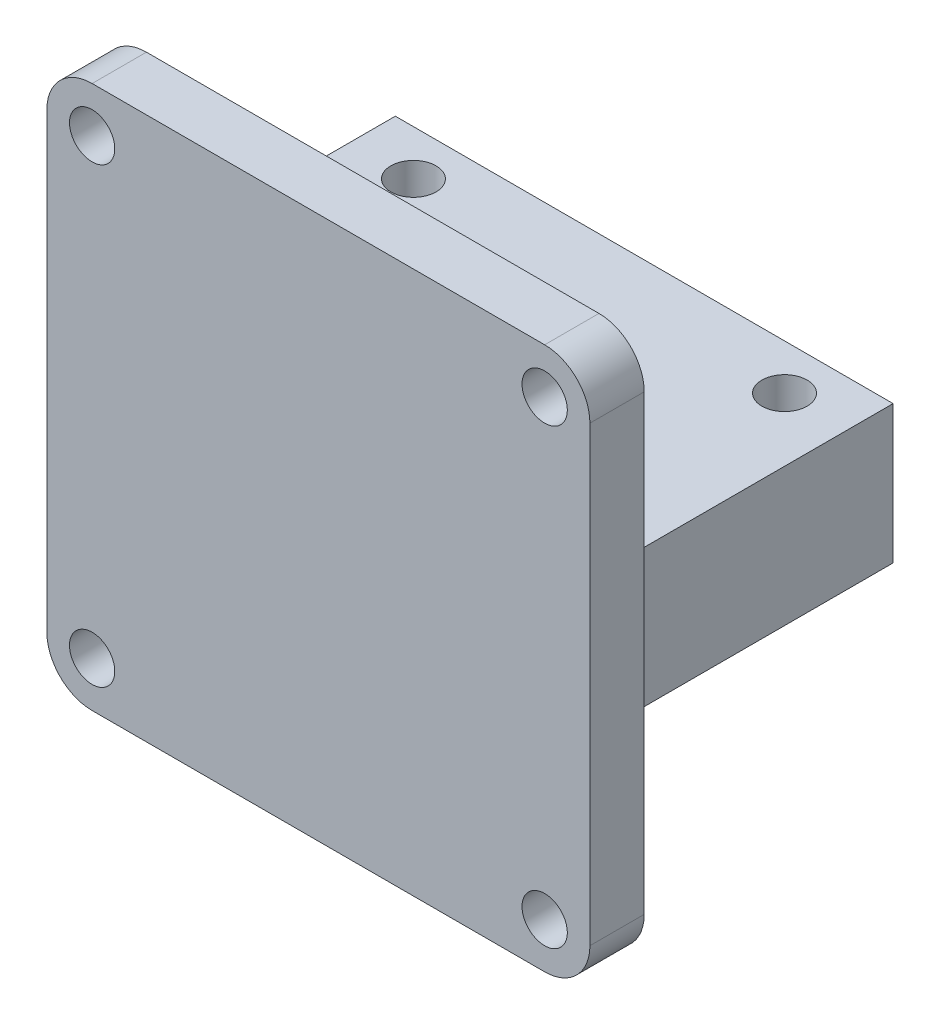
SolidWorks part; units mm, degrees
ref_plane "Front Plane" through (0, 0, 0) normal (0, 0, 1) x (1, 0, 0)
ref_plane "Top Plane" through (0, 0, 0) normal (0, 1, 0) x (1, 0, 0)
ref_plane "Right Plane" through (0, 0, 0) normal (1, 0, 0) x (0, 0, -1)
sketch "Sketch1" plane through (0, 0, 0) normal (0, 0, 1) x (1, 0, 0)
  line L1 (-30, 30) -> (30, 30)
  line L2 (-30, 30) -> (-30, -30)
  line L3 (-30, -30) -> (30, -30)
  line L4 (30, 30) -> (30, -30)
  line L5 (-30, 30) -> (30, -30) construction
  line L6 (-30, -30) -> (30, 30) construction
  point P0 (0, 0)
  dimension "D1" = 60
  dimension "D2" = 60
extrude "Boss-Extrude1" add sketch "Sketch1" along normal blind 6
sketch "Sketch2" plane through (0, 0, 0) normal (0, 0, -1) x (-1, 0, 0)
  line L1 (-27.5, 7.625) -> (27.5, 7.625)
  line L2 (-27.5, 7.625) -> (-27.5, -7.625)
  line L3 (-27.5, -7.625) -> (27.5, -7.625)
  line L4 (27.5, 7.625) -> (27.5, -7.625)
  line L5 (-27.5, 7.625) -> (27.5, -7.625) construction
  line L6 (-27.5, -7.625) -> (27.5, 7.625) construction
  point P0 (0, 0)
  dimension "D1" = 15.25
  dimension "D2" = 55
extrude "Boss-Extrude2" add sketch "Sketch2" along normal blind 30
hole_wizard "Ø5.0mm Dowel Hole1" positions "Sketch5" profile "Sketch6" hole size "Ø5.0" standard "DIN" end condition through all
sketch "Sketch5" plane through (0, 0, 0) normal (0, 0, -1) x (-1, 0, 0)
  line L0 (0, 30) -> (0, -30) construction
  line L1 (-30, 30) -> (30, 30) construction
  line L2 (30, -30) -> (-30, -30) construction
  line L4 (-30, 0) -> (30, 0) construction
  line L5 (-30, -30) -> (-30, 30) construction
  line L6 (30, 30) -> (30, -30) construction
  point P0 (25, 25)
  point P19 (0, 0)
  point P20 (-25, 25)
  point P21 (25, -25)
  point P22 (-25, -25)
  dimension "D1" = 5
  dimension "D2" = 5
sketch "Sketch6" plane through (-25, 25, 0) normal (1, 0, 0) x (0, 1, 0)
  line L0 (0, 0) -> (0, 6)
  line L1 (0, 6) -> (2.5, 6)
  line L2 (2.5, 6) -> (2.5, 0)
  line L5 (2.5, 0) -> (0, 0)
  line L11 (0, -6.35) -> (0, 107.95) construction
  dimension "Thru Hole Dia." = 5
  dimension "Thru Hole Depth" = 6
fillet "Fillet1" radius 5 4 edges at (-30, 30, 3) (-30, -30, 3) (30, -30, 3) (30, 30, 3)
hole_wizard "Ø5.0mm Dowel Hole2" positions "Sketch7" profile "Sketch8" hole size "Ø5.0" standard "DIN" end condition through all
sketch "Sketch7" plane through (0, 7.625, 0) normal (0, 1, 0) x (1, 0, 0)
  line L0 (27.5, 15) -> (-27.5, 15) construction
  line L1 (27.5, 30) -> (27.5, 0) construction
  line L2 (-27.5, 30) -> (-27.5, 0) construction
  line L4 (0, 0) -> (0, 30) construction
  line L5 (-27.5, 0) -> (27.5, 0) construction
  line L6 (-27.5, 30) -> (27.5, 30) construction
  point P0 (20.5, 25)
  point P18 (20.5, 5)
  point P19 (-20.5, 5)
  point P20 (-20.5, 25)
  dimension "D1" = 7
  dimension "D2" = 5
sketch "Sketch8" plane through (20.5, 7.625, -25) normal (1, 0, 0) x (0, 0, 1)
  line L0 (0, 0) -> (0, 37.625)
  line L1 (0, 37.625) -> (2.5, 37.625)
  line L2 (2.5, 37.625) -> (2.5, 0)
  line L5 (2.5, 0) -> (0, 0)
  line L11 (0, -6.35) -> (0, 107.95) construction
  dimension "Thru Hole Dia." = 5
  dimension "Thru Hole Depth" = 37.625
